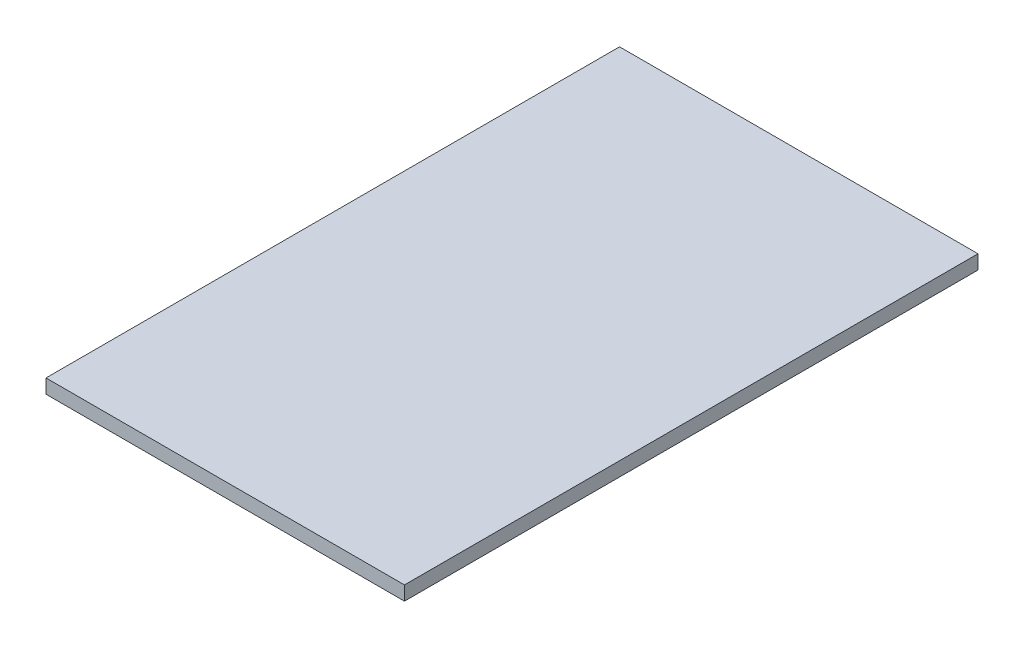
SolidWorks part; units mm, degrees
ref_plane "Front Plane" through (0, 0, 0) normal (0, 0, 1) x (1, 0, 0)
ref_plane "Top Plane" through (0, 0, 0) normal (0, 1, 0) x (1, 0, 0)
ref_plane "Right Plane" through (0, 0, 0) normal (1, 0, 0) x (0, 0, -1)
sketch "Sketch1" plane through (0, 0, 0) normal (0, 1, 0) x (1, 0, 0)
  line L1 (-127, -203.2) -> (127, -203.2)
  line L2 (-127, -203.2) -> (-127, 203.2)
  line L3 (-127, 203.2) -> (127, 203.2)
  line L4 (127, -203.2) -> (127, 203.2)
  line L5 (-127, -203.2) -> (127, 203.2) construction
  line L6 (-127, 203.2) -> (127, -203.2) construction
  point P0 (0, 0)
  dimension "D1" = 406.4
  dimension "D2" = 254
extrude "Boss-Extrude1" add sketch "Sketch1" along normal blind 10
